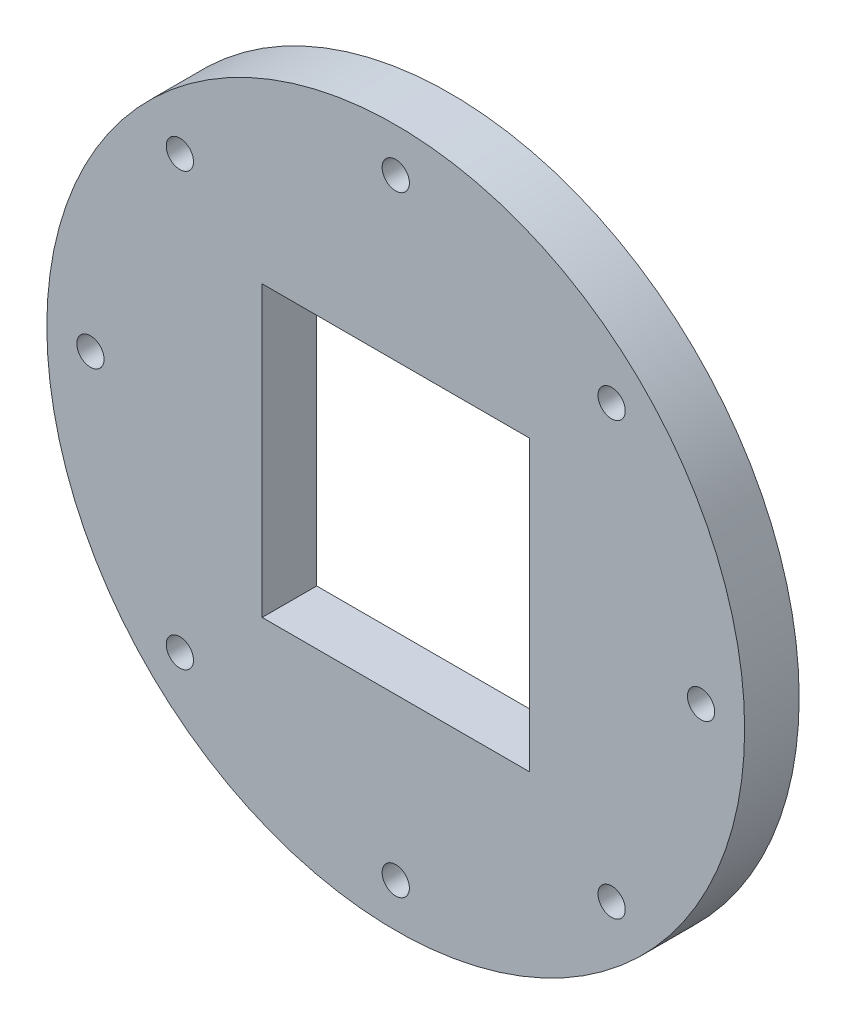
SolidWorks part; units mm, degrees
ref_plane "Alzado" through (0, 0, 0) normal (0, 0, 1) x (1, 0, 0)
ref_plane "Planta" through (0, 0, 0) normal (0, 1, 0) x (1, 0, 0)
ref_plane "Vista lateral" through (0, 0, 0) normal (1, 0, 0) x (0, 0, -1)
sketch "Croquis1" plane through (0, 0, 0) normal (0, 0, 1) x (1, 0, 0)
  circle A0 centre (0, 0) radius 32
  dimension "D1" = 64
extrude "Saliente-Extruir1" add sketch "Croquis1" along normal blind 5
sketch "Croquis2" plane through (0, 0, 5) normal (0, 0, 1) x (1, 0, 0)
  line L0 (0, 0) -> (0, 28) construction
  line L1 (0, 0) -> (19.799, 19.799) construction
  line L2 (0, 0) -> (28, 0) construction
  line L3 (0, 0) -> (19.799, -19.799) construction
  line L4 (0, 0) -> (0, -28) construction
  line L5 (0, 0) -> (-19.799, -19.799) construction
  line L6 (0, 0) -> (-28, 0) construction
  line L7 (0, 0) -> (-19.799, 19.799) construction
  circle A0 centre (0, 28) radius 1.25
  circle A1 centre (0, 0) radius 32 construction
  circle A2 centre (19.799, 19.799) radius 1.25
  circle A3 centre (28, 0) radius 1.25
  circle A4 centre (19.799, -19.799) radius 1.25
  circle A5 centre (0, -28) radius 1.25
  circle A6 centre (-19.799, -19.799) radius 1.25
  circle A7 centre (-28, 0) radius 1.25
  circle A8 centre (-19.799, 19.799) radius 1.25
  point P19 (0, 0)
  dimension "D1" = 2.5
  dimension "D2" = 28
  dimension "D3" = 8
extrude "Cortar-Extruir1" cut sketch "Croquis2" against normal through all
sketch "Croquis3" plane through (0, 0, 5) normal (0, 0, 1) x (1, 0, 0)
  line L0 (0, 32) -> (0, -32) construction
  line L1 (-12.25, -13.25) -> (-12.25, 13.25)
  line L2 (-12.25, -13.25) -> (12.25, -13.25)
  line L3 (12.25, -13.25) -> (12.25, 13.25)
  line L4 (-12.25, 13.25) -> (12.25, 13.25)
  line L5 (-12.25, -13.25) -> (12.25, 13.25) construction
  line L6 (12.25, -13.25) -> (-12.25, 13.25) construction
  circle A0 centre (0, 0) radius 32 construction
  point P0 (0, 0)
  dimension "D1" = 24.5
  dimension "D2" = 26.5
  dimension "D3" = 0
extrude "Cortar-Extruir2" cut sketch "Croquis3" against normal blind 10
sketch "Croquis4" plane through (0, 0, 0) normal (0, 0, -1) x (-1, 0, 0)
  line L0 (-14.1, 15.4) -> (14.4, 15.4) construction
  line L1 (-14.1, -13.1) -> (-14.1, 15.4) construction
  circle A0 centre (-10.1, 23.4) radius 5
  dimension "D1" = 10
  dimension "D2" = 8
  dimension "D3" = 4
extrude "Cortar-Extruir3" [suppressed] cut sketch "Croquis4" against normal blind 10
